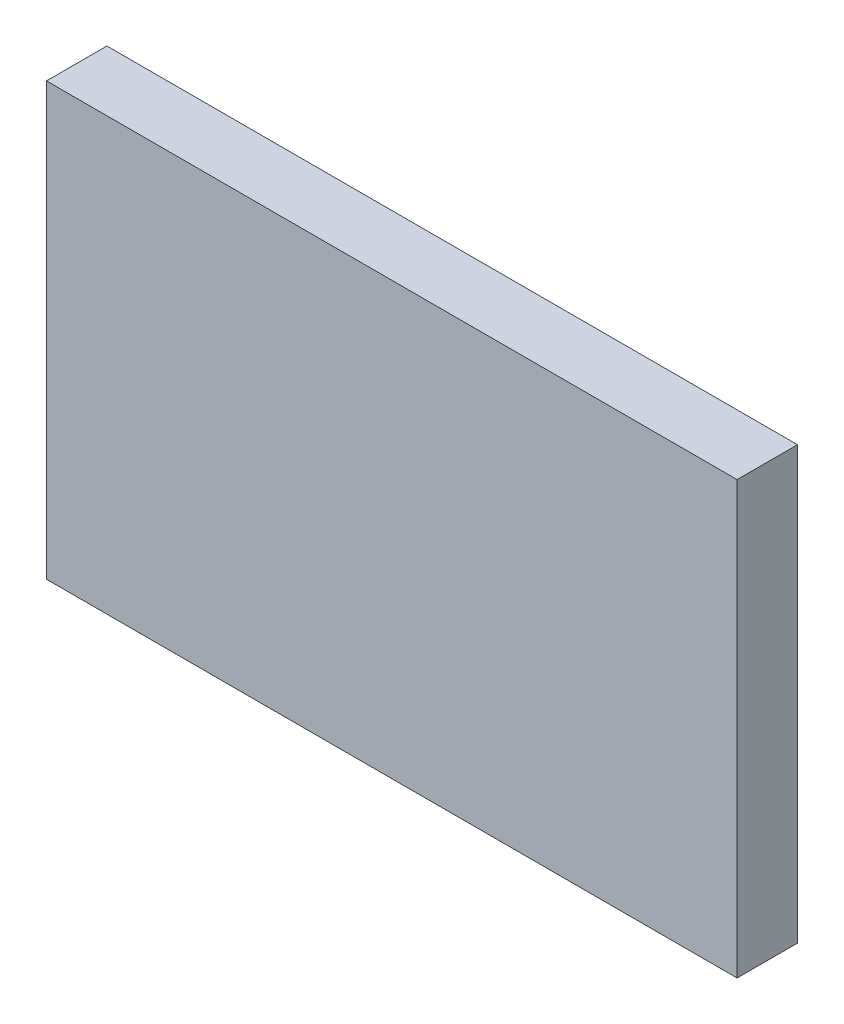
SolidWorks part; units mm, degrees
material "Mahogany"
ref_plane "Front Plane" through (0, 0, 0) normal (0, 0, 1) x (1, 0, 0)
ref_plane "Top Plane" through (0, 0, 0) normal (0, 1, 0) x (1, 0, 0)
ref_plane "Right Plane" through (0, 0, 0) normal (1, 0, 0) x (0, 0, -1)
sketch "Sketch4" plane through (0, 0, 0) normal (0, 0, 1) x (1, 0, 0)
  line L1 (-40, 25) -> (40, 25)
  line L2 (-40, 25) -> (-40, -25)
  line L3 (-40, -25) -> (40, -25)
  line L4 (40, 25) -> (40, -25)
  line L5 (-40, 25) -> (40, -25) construction
  line L6 (-40, -25) -> (40, 25) construction
  point P0 (0, 0)
  dimension "D1" = 80
  dimension "D2" = 50
extrude "Boss-Extrude2" add sketch "Sketch4" against normal blind 7
sketch "Sketch8" plane through (0, 0, -7) normal (0, 0, -1) x (-1, 0, 0)
  line L0 (-30, 0) -> (30, 0) construction
  line L1 (-30, 4) -> (30, 4)
  line L2 (-30, -4) -> (30, -4)
  line L3 (40, 25) -> (40, -25) construction
  line L4 (-40, -25) -> (-40, 25) construction
  arc A0 (-30, 4) -> (-30, -4) centre (-30, 0) ccw
  arc A1 (30, -4) -> (30, 4) centre (30, 0) ccw
  point P3 (0, 0)
  dimension "D1" = 4
  dimension "D2" = 10
  dimension "D3" = 10
extrude "Cut-Extrude2" cut sketch "Sketch8" against normal offset from surface (4 mm away) 3 up to face at (0, 0, 0)
sketch "Sketch9" plane through (0, 0, -3) normal (0, 0, -1) x (-1, 0, 0)
  line L0 (-30, 0) -> (30, 0) construction
